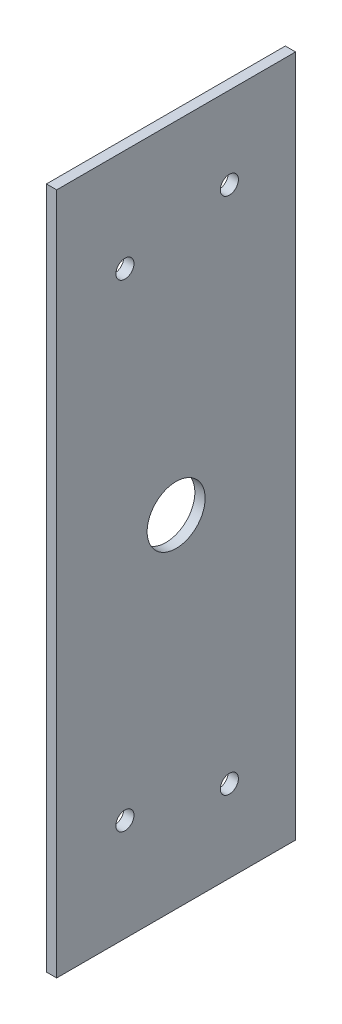
SolidWorks part; units mm, degrees
ref_plane "Front Plane" through (0, 0, 0) normal (1, 0, 0) x (0, 1, 0)
ref_plane "Top Plane" through (0, 0, 0) normal (0, 0, 1) x (0, 1, 0)
ref_plane "Right Plane" through (0, 0, 0) normal (0, 1, 0) x (-1, 0, 0)
sketch "Sketch1" plane through (0, 0, 0) normal (1, 0, 0) x (0, 1, 0)
  line L0 (0, 81.4023) -> (0, 28) construction
  line L1 (-100, 35) -> (100, 35)
  line L2 (-100, 35) -> (-100, -35)
  line L3 (-100, -35) -> (100, -35)
  line L4 (100, 35) -> (100, -35)
  line L13 (-217.085, 0) -> (250.2284, 0) construction
  line L30 (0, 25) -> (0, -25) construction
  line L31 (0, -35) -> (0, -114.8153) construction
  circle A0 centre (0, 0) radius 8.5
  circle A1 centre (-76, -15.6) radius 2.65
  circle A3 centre (76, -15.6) radius 2.65
  circle A4 centre (-70, 15) radius 2.65
  circle A5 centre (70, 15) radius 2.65
  point P4 (0, 35)
  point P6 (-100, 0)
  dimension "D1" = 17
  dimension "D2" = 5.3
  dimension "D13" = 5.3
  dimension "D3" = 20
  dimension "D7" = 76
  dimension "D8" = 15.6
  dimension "D11" = 200
  dimension "D12" = 70
  dimension "D15" = 30
extrude "Boss-Extrude1" add sketch "Sketch1" along normal blind 3
